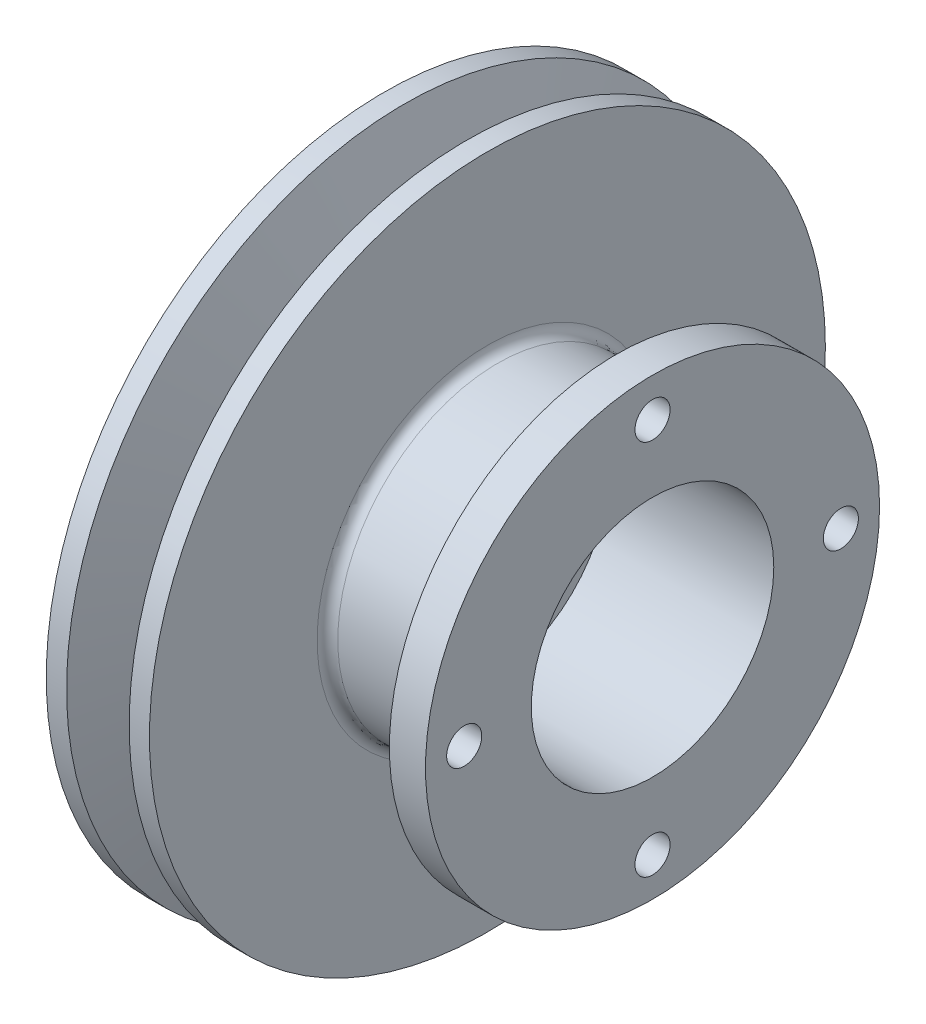
SolidWorks part; units mm, degrees
material "Cast Alloy Steel"
ref_plane "Front Plane" through (0, 0, 0) normal (0, 0, 1) x (1, 0, 0)
ref_plane "Top Plane" through (0, 0, 0) normal (0, 1, 0) x (1, 0, 0)
ref_plane "Right Plane" through (0, 0, 0) normal (1, 0, 0) x (0, 0, -1)
sketch "Sketch1" plane through (0, 0, 0) normal (0, 0, 1) x (1, 0, 0)
  line L0 (0, 0) -> (-141.2992, 0) construction
  line L1 (0, 0) -> (0, 44)
  line L2 (0, 44) -> (-7, 44)
  line L3 (-7, 44) -> (-7, 31)
  line L4 (-7, 31) -> (-32, 31)
  line L5 (-32, 31) -> (-32, 65.5)
  line L6 (-32, 65.5) -> (-35.9379, 65.5)
  line L7 (-35.9379, 65.5) -> (-39.9994, 53)
  line L8 (-39.9994, 53) -> (-44.0006, 53)
  line L9 (-44.0006, 53) -> (-48.0621, 65.5)
  line L10 (-48.0621, 65.5) -> (-52, 65.5)
  line L11 (-52, 65.5) -> (-52, 46)
  line L12 (-52, 46) -> (-39, 46)
  line L13 (-39, 46) -> (-39, 38)
  line L14 (-39, 38) -> (-66, 38)
  line L15 (-66, 38) -> (-66, 0)
  line L16 (-66, 0) -> (0, 0)
  line L17 (-42, 53) -> (-42, 79.7403) construction
  line L18 (-89.1415, 61) -> (-25.1332, 61) construction
  point P22 (-46.6, 61)
  point P23 (-37.4, 61)
  dimension "D1" = 76
  dimension "D2" = 92
  dimension "D3" = 131
  dimension "D4" = 62
  dimension "D5" = 88
  dimension "D6" = 106
  dimension "D7" = 36
  dimension "D8" = 20
  dimension "D9" = 66
  dimension "D10" = 7
  dimension "D11" = 24
  dimension "D12" = 27
  dimension "D13" = 61
  dimension "D14" = 4.5
  dimension "D15" = 8
  dimension "D16" = 18
  dimension "D17" = 9.2
revolve "Revolve1" add sketch "Sketch1" angle 360 about L0
sketch "Sketch2" plane through (0, 0, 0) normal (0, 0, 1) x (1, 0, 0)
  line L0 (0, 0) -> (-115.5596, 0) construction
  line L1 (0, 0) -> (0, 23.5)
  line L2 (0, -44) -> (0, 44) construction
  line L3 (0, 23.5) -> (-32, 23.5)
  line L4 (-32, 23.5) -> (-32, 20)
  line L5 (-32, 20) -> (-36, 20)
  line L6 (-36, 20) -> (-39, 23)
  line L9 (-55, 34) -> (-58, 34)
  line L10 (-58, 34) -> (-58, 30)
  line L11 (-58, 30) -> (-66, 30)
  line L12 (-66, 38) -> (-66, -38) construction
  line L13 (-66, 30) -> (-66, 0)
  line L14 (-66, 0) -> (0, 0)
  line L15 (-55, 34) -> (-55, 31)
  line L16 (-55, 31) -> (-39, 31)
  line L17 (-39, 31) -> (-39, 23)
  point P3 (-56.5, 34)
  dimension "D1" = 68
  dimension "D2" = 47
  dimension "D3" = 40
  dimension "D4" = 46
  dimension "D5" = 62
  dimension "D6" = 32
  dimension "D7" = 4
  dimension "D8" = 27
  dimension "3" = 3
  dimension "D9" = 16
  dimension "D10" = 60
revolve "Cut-Revolve1" cut sketch "Sketch2" angle 360 about L0
cosmetic thread "Cosmetic Thread1" parameters "D2"=64
chamfer "Chamfer1" distance 1 angle 45 1 edges at (-55, 0, -31)
fillet "Fillet1" radius 2 5 edges at (-7, 0, -31) (-32, 0, -31) (-52, 0, -46) (-39, 0, -38) (-39, 0, -46)
hole_wizard "M8 Tapped Hole1" positions "Sketch3" profile "Sketch4" tap size "M8" standard "KS"
sketch "Sketch3" plane through (0, 0, 0) normal (1, 0, 0) x (0, 0, -1)
  circle A0 centre (0, 0) radius 36.5 construction
  point P0 (0, 36.5)
  dimension "D1" = 73
sketch "Sketch4" plane through (0, 36.5, 0) normal (0, 1, 0) x (0, 0, -1)
  line L0 (0, 0) -> (0, 9.0429)
  line L1 (0, 9.0429) -> (3.4, 7)
  line L2 (3.4, 7) -> (3.4, 0)
  line L5 (3.4, 0) -> (0, 0)
  line L10 (0, 9.0429) -> (-3.4, 7) construction
  line L11 (0, -6.35) -> (0, 107.95) construction
  dimension "Tap Drill Dia." = 6.8
  dimension "Tap Drill Depth" = 7
  dimension "Drill Angle" = 118
cosmetic thread "Hole Thread1" parameters "D1"=7, "D2"=8
pattern_circular "CirPattern1" count 4 over 360 about axis through (0, 0, 0) along (1, 0, 0) of "M8 Tapped Hole1"
cosmetic thread "Hole Thread2" parameters "D1"=7, "D2"=8
cosmetic thread "Hole Thread3" parameters "D1"=7, "D2"=8
cosmetic thread "Hole Thread4" parameters "D1"=7, "D2"=8
